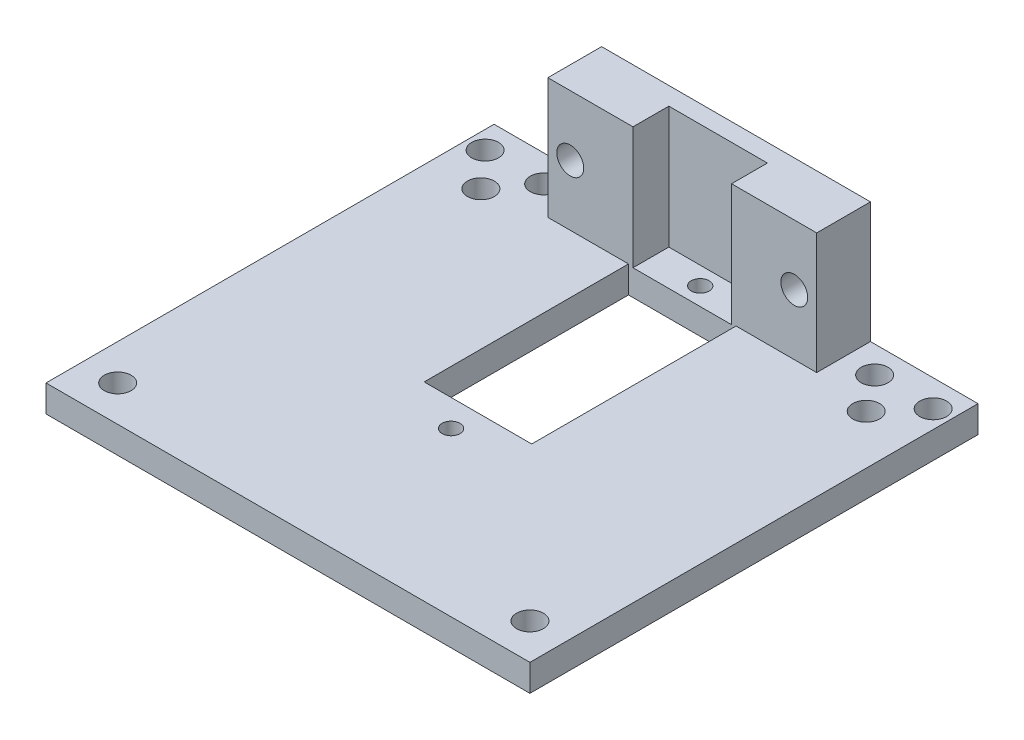
SolidWorks part; units mm, degrees
ref_plane "Front Plane" through (0, 0, 0) normal (0, 0, 1) x (1, 0, 0)
ref_plane "Top Plane" through (0, 0, 0) normal (0, 1, 0) x (1, 0, 0)
ref_plane "Right Plane" through (0, 0, 0) normal (1, 0, 0) x (0, 0, -1)
sketch "Sketch1" plane through (0, 0, 0) normal (0, 0, 1) x (1, 0, 0)
  line L0 (0, 0) -> (-4, 0)
  line L1 (-4, 0) -> (-4, 20)
  line L2 (-4, 20) -> (8, 20)
  line L3 (8, 20) -> (8, 33.5)
  line L4 (8, 33.5) -> (38, 33.5)
  line L5 (38, 33.5) -> (38, 20)
  line L6 (38, 20) -> (50, 20)
  line L7 (50, 20) -> (50, 0)
  line L8 (50, 0) -> (46, 0)
  line L9 (46, 0) -> (46, 17)
  line L10 (46, 17) -> (0, 17)
  line L11 (0, 17) -> (0, 0)
  line L13 (38, 26.75) -> (35.5, 26.75) construction
  line L14 (23, 33.5) -> (23, 21.5089) construction
  circle A0 centre (10.5, 26.75) radius 1.5
  circle A1 centre (35.5, 26.75) radius 1.5
  point P9 (-2, 0)
  point P14 (48, 0)
  dimension "D9" = 3
  dimension "D1" = 4
  dimension "D2" = 50
  dimension "D3" = 20
  dimension "D4" = 3
  dimension "D5" = 30
  dimension "D6" = 13.5
  dimension "D8" = 2.5
extrude "Boss-Extrude1" add sketch "Sketch1" along normal blind 6
ref_plane "Plane1" through (0, 0, 0) normal (0, 0, 1) x (1, 0, 0)
sketch "Sketch2" plane through (0, 0, 0) normal (0, 0, 1) x (1, 0, 0)
  line L0 (-4, 17) -> (-4, 20)
  line L1 (-4, 20) -> (-4, 0) construction
  line L2 (-4, 20) -> (50, 20)
  line L3 (50, 20) -> (50, 17)
  line L4 (50, 0) -> (50, 20) construction
  line L5 (50, 17) -> (-4, 17)
extrude "Boss-Extrude2" add sketch "Sketch2" along normal blind 50
sketch "Sketch3" plane through (0, 20, 0) normal (0, 1, 0) x (1, 0, 0)
  line L0 (23, -50) -> (23, -42.0069) construction
  line L8 (-4, -50) -> (-4, 0) construction
  line L9 (50, -50) -> (-4, -50) construction
  circle A1 centre (0, -46) radius 1.5
  circle A2 centre (46, -46) radius 1.5
  dimension "D4" = 3
  dimension "D1" = 4
  dimension "D2" = 4
sketch "Sketch4" plane through (0, 20, 0) normal (0, 1, 0) x (1, 0, 0)
  line L0 (-18.425, 0) -> (18.425, 0) construction
  line L2 (-4, -50) -> (-4, 0) construction
  line L3 (23, -6) -> (23, 2.98) construction
  line L4 (38, -6) -> (8, -6) construction
  line L5 (17, -6) -> (17, -28.8)
  line L6 (17, -28.8) -> (29, -28.8)
  line L7 (29, -28.8) -> (29, -6)
  line L8 (29, -6) -> (17, -6)
  circle A0 centre (4.534, -3) radius 1.5
  circle A1 centre (1.5, -6.9742) radius 1.5
  circle A2 centre (41.466, -3) radius 1.5
  circle A3 centre (44.5, -6.9742) radius 1.5
  circle A4 centre (23, -31.8) radius 1
  dimension "D3" = 3
  dimension "D4" = 3
  dimension "D8" = 2
  dimension "D9" = 3
  dimension "D1" = 3
  dimension "D2" = 5.5
  dimension "D5" = 5
  dimension "D6" = 22.8
  dimension "D7" = 12
extrude "Cut-Extrude1" cut sketch "Sketch4" against normal blind 24
sketch "Sketch5" plane through (0, 33.5, 0) normal (0, 1, 0) x (1, 0, 0)
  line L0 (28.5, -6) -> (28.5, -2)
  line L1 (38, -6) -> (8, -6) construction
  line L2 (28.5, -2) -> (17.5, -2)
  line L3 (17.5, -2) -> (17.5, -6)
  line L4 (17.5, -6) -> (28.5, -6)
  line L5 (38, -6) -> (38, 0) construction
  point P4 (23, -6)
  dimension "D3" = 15
  dimension "D1" = 11
  dimension "D2" = 4
extrude "Cut-Extrude2" cut sketch "Sketch5" against normal blind 13.62 contours L4 L0 L2 L3
sketch "Sketch6" plane through (0, 19.88, 0) normal (0, 1, 0) x (1, 0, 0)
  line L0 (28.5, -2) -> (17.5, -2) construction
  line L2 (28.5, -6) -> (28.5, -2) construction
  circle A0 centre (23, -4) radius 1
  dimension "D1" = 2
  dimension "D2" = 2
  dimension "D3" = 5.5
extrude "Cut-Extrude3" cut sketch "Sketch6" against normal blind 24
sketch "Sketch7" plane through (0, 0, 0) normal (0, -1, 0) x (1, 0, 0)
  line L0 (50, 6) -> (50, 0) construction
  line L2 (46, 6) -> (50, 6) construction
  circle A0 centre (48, 3) radius 1.5
  dimension "D1" = 3
  dimension "D2" = 2
  dimension "D3" = 3
extrude "Cut-Extrude4" cut sketch "Sketch7" against normal blind 7
sketch "Sketch8" plane through (0, 0, 0) normal (0, -1, 0) x (1, 0, 0)
  line L0 (-4, 6) -> (-4, 0) construction
  line L2 (-4, 6) -> (0, 6) construction
  circle A0 centre (-2, 3) radius 1.5
  dimension "D1" = 3
  dimension "D2" = 2
  dimension "D3" = 3
extrude "Cut-Extrude5" cut sketch "Sketch8" against normal blind 7
extrude "Cut-Extrude6" cut sketch "Sketch3" against normal blind 60
sketch "Sketch9" plane through (0, 17, 0) normal (0, -1, 0) x (1, 0, 0)
  circle A0 centre (48, 3) radius 1.5
  circle A1 centre (-2, 3) radius 1.5
extrude "Cut-Extrude7" cut sketch "Sketch9" against normal blind 10
ref_plane "Plane2" through (0, 17, 0) normal (0, -1, 0) x (-1, 0, 0)
other "SurfaceCut1"
